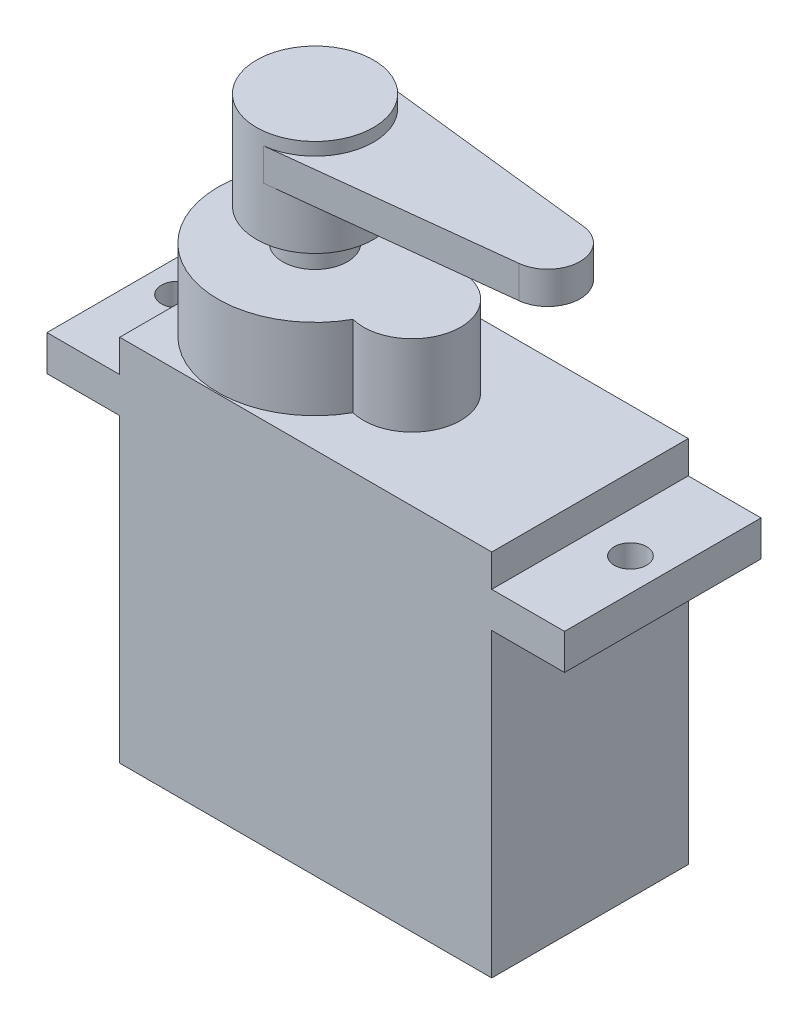
SolidWorks part; units mm, degrees
ref_plane "Front Plane" through (0, 0, 0) normal (0, 0, 1) x (1, 0, 0)
ref_plane "Top Plane" through (0, 0, 0) normal (0, 1, 0) x (1, 0, 0)
ref_plane "Right Plane" through (0, 0, 0) normal (1, 0, 0) x (0, 0, -1)
sketch "Sketch3" plane through (0, 0, 0) normal (0, 0, 1) x (1, 0, 0)
  line L0 (8.8736, -19.2745) -> (-14.1264, -19.2745)
  line L1 (-14.1264, -19.2745) -> (-14.1264, -0.6645)
  line L2 (-14.1264, -0.6645) -> (-18.6264, -0.6645)
  line L3 (-18.6264, -0.6645) -> (-18.6264, 1.5355)
  line L4 (-18.6264, 1.5355) -> (-14.1264, 1.5355)
  line L5 (-14.1264, 1.5355) -> (-14.1264, 3.5355)
  line L6 (-14.1264, 3.5355) -> (8.8736, 3.5355)
  line L7 (8.8736, 3.5355) -> (8.8736, 1.5355)
  line L8 (8.8736, 1.5355) -> (13.3736, 1.5355)
  line L9 (13.3736, 1.5355) -> (13.3736, -0.6645)
  line L10 (13.3736, -0.6645) -> (8.8736, -0.6645)
  line L11 (8.8736, -0.6645) -> (8.8736, -19.2745)
  dimension "D1" = 18.61
  dimension "D2" = 18.61
  dimension "D3" = 23
  dimension "D4" = 90
  dimension "D5" = 4.5
  dimension "D6" = 4.5
  dimension "D7" = 2.2
  dimension "D8" = 2.2
  dimension "D9" = 4.5
  dimension "D10" = 4.5
  dimension "D11" = 2
extrude "Boss-Extrude1" add sketch "Sketch3" along normal blind 12.15
sketch "Sketch4" plane through (0, 1.5355, 0) normal (0, 1, 0) x (1, 0, 0)
  line L0 (-18.6264, -12.15) -> (-18.6264, 0) construction
  line L1 (13.3736, -12.15) -> (13.3736, 0) construction
  circle A0 centre (-16.6264, -6.075) radius 1
  circle A1 centre (11.3736, -6.075) radius 1
  dimension "D1" = 2
  dimension "D2" = 2
extrude "Cut-Extrude1" cut sketch "Sketch4" against normal blind 12.15
sketch "Sketch5" plane through (0, 3.5355, 0) normal (0, 1, 0) x (1, 0, 0)
  line L0 (-8.1264, -6.075) -> (-14.1264, -6.075) construction
  line L1 (-14.1264, -12.15) -> (-14.1264, 0) construction
  circle A0 centre (-8.1264, -6.075) radius 6
  circle A1 centre (-2.1264, -6.075) radius 3
  point P7 (-2.1264, -6.075)
  dimension "D1" = 6
  dimension "D2" = 12
extrude "Boss-Extrude2" add sketch "Sketch5" along normal blind 5
sketch "Sketch6" plane through (0, 8.5355, 0) normal (0, 1, 0) x (1, 0, 0)
  circle A0 centre (-8.1264, -6.075) radius 2
extrude "Boss-Extrude3" add sketch "Sketch6" along normal blind 2
sketch "Sketch7" plane through (0, 10.5355, 0) normal (0, 1, 0) x (1, 0, 0)
  circle A0 centre (-8.1264, -6.075) radius 3.615
  dimension "D1" = 7.23
extrude "Boss-Extrude4" add sketch "Sketch7" along normal blind 6
sketch "Sketch8" plane through (0, 16.5355, 0) normal (0, 1, 0) x (1, 0, 0)
  line L0 (-11.7414, -6.075) -> (8.2586, -6.075) construction
  line L1 (-7.7205, -2.4829) -> (6.4831, -4.0876)
  line L2 (6.4831, -8.0624) -> (-7.7205, -9.6671)
  circle A0 centre (-8.1264, -6.075) radius 3.615 construction
  circle A1 centre (6.2586, -6.075) radius 2
  circle A2 centre (-8.1264, -6.075) radius 3.615
  circle M4 centre (-8.1264, -6.075) radius 3.615
  dimension "D2" = 4
  dimension "D3" = 7.23
  dimension "D1" = 20
extrude "Boss-Extrude5" add sketch "Sketch8" against normal blind 2 from offset 0.79 contours A2 L0 A1 L1 | L0 L2 A1 M4 | A1 L0 | L0 A1
